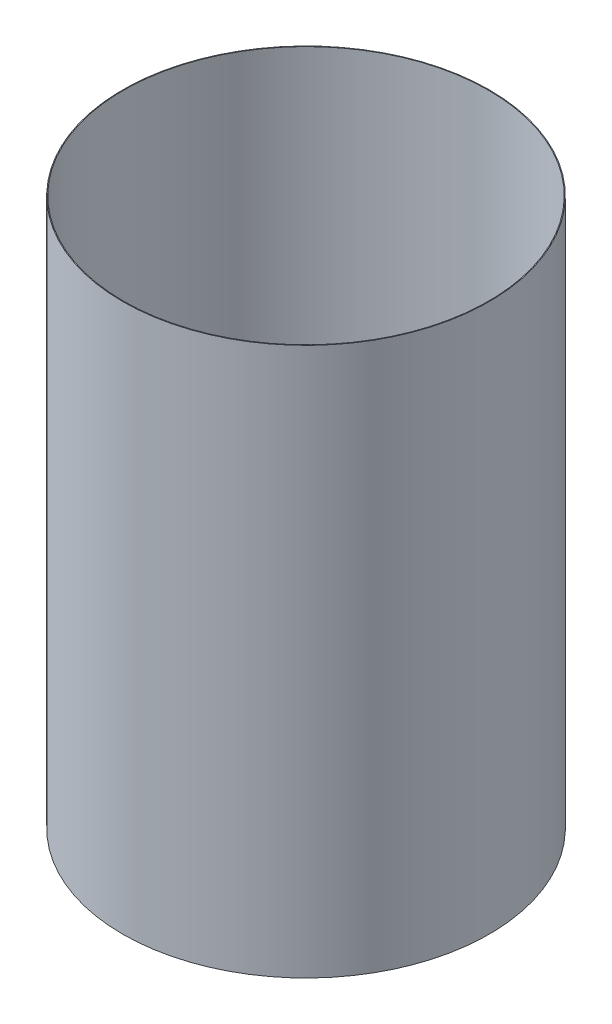
SolidWorks part; units mm, degrees
ref_plane "Front Plane" through (0, 0, 0) normal (0, 0, 1) x (1, 0, 0)
ref_plane "Top Plane" through (0, 0, 0) normal (0, 1, 0) x (1, 0, 0)
ref_plane "Right Plane" through (0, 0, 0) normal (1, 0, 0) x (0, 0, -1)
ref_plane "Plane1" through (0, 1800, 0) normal (0, 1, 0) x (1, 0, 0)
sketch "Sketch1" plane through (0, 1800, 0) normal (0, 1, 0) x (1, 0, 0)
  circle A0 centre (0, 0) radius 500
  circle A1 centre (0, 0) radius 502
extrude "Boss-Extrude1" add sketch "Sketch1" along normal blind 1500
